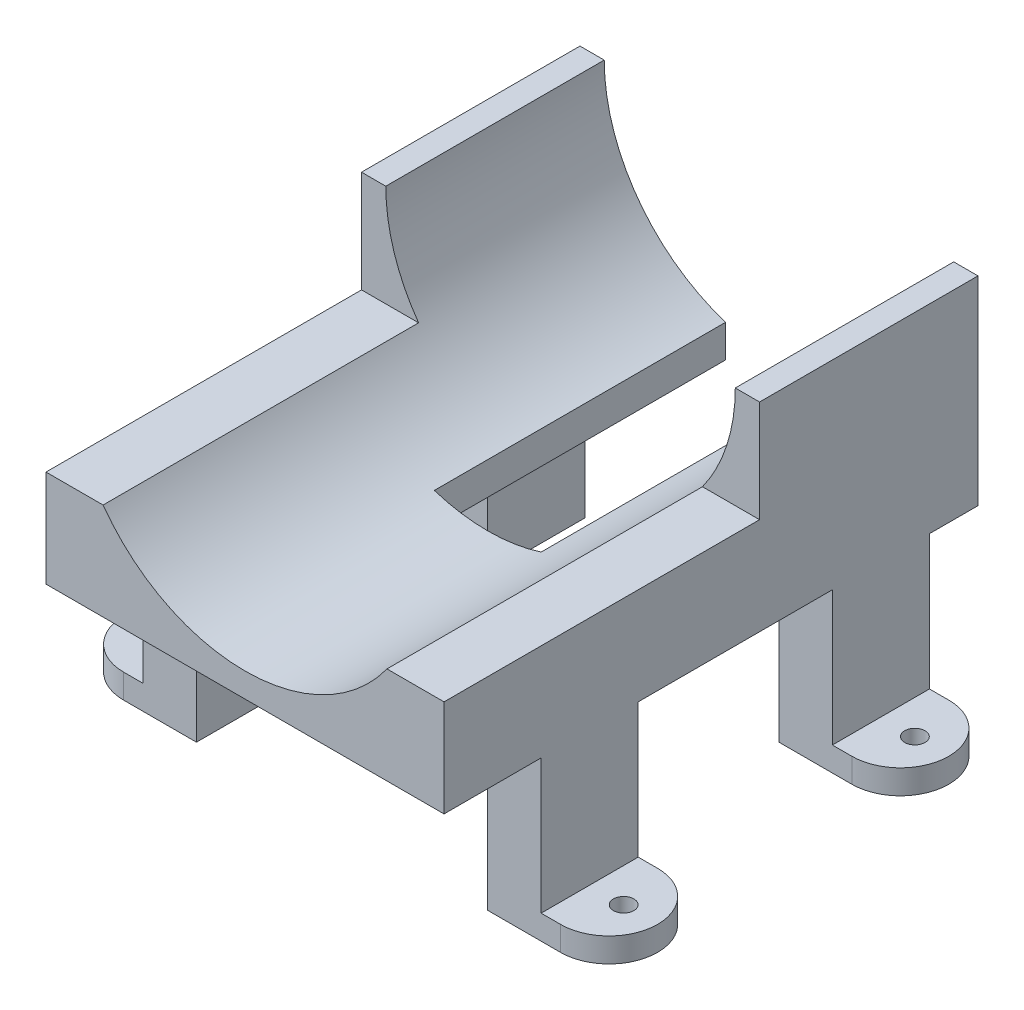
SolidWorks part; units mm, degrees
ref_plane "前基準面" through (0, 0, 0) normal (0, 0, 1) x (1, 0, 0)
ref_plane "上基準面" through (0, 0, 0) normal (0, 1, 0) x (1, 0, 0)
ref_plane "右基準面" through (0, 0, 0) normal (1, 0, 0) x (0, 0, -1)
sketch "草圖1" plane through (0, 0, 0) normal (0, 0, 1) x (1, 0, 0)
  line L0 (-41, 0) -> (41, 0) construction
  line L1 (-41, 0) -> (-41, -41)
  line L2 (-41, -41) -> (41, -41)
  line L3 (41, -41) -> (41, 0)
  circle A0 centre (0, 0) radius 36
  arc A1 (41, 0) -> (-41, 0) centre (0, 0) ccw
  circle A2 centre (0, 0) radius 41 construction
  dimension "D1" = 72
  dimension "D2" = 5
extrude "填料-伸長1" add sketch "草圖1" along normal blind 90
sketch "草圖2" plane through (0, 0, 0) normal (0, 0, 1) x (1, 0, 0)
  line L0 (0, 42.9462) -> (0, -46.3268) construction
  line L2 (11, -34.2783) -> (-11, -34.2783)
  line L3 (11, -34.2783) -> (11, -41)
  line L4 (11, -41) -> (-11, -41)
  line L5 (-11, -34.2783) -> (-11, -41)
  line L6 (0, -41) -> (0, -34.2783) construction
  line L7 (11, -37.6391) -> (-11, -37.6391) construction
  circle A0 centre (0, 0) radius 36 construction
  circle A1 centre (0, 0) radius 41 construction
  point P3 (0, -37.6391)
  dimension "D1" = 22
extrude "除料-伸長1" cut sketch "草圖2" along normal blind 60
sketch "草圖3" plane through (0, 0, 0) normal (1, 0, 0) x (0, 0, -1)
  line L1 (0, 41) -> (-90, 41)
  line L2 (0, 41) -> (0, 0)
  line L3 (0, 0) -> (-45, 0)
  line L4 (-90, 41) -> (-90, -21)
  line L5 (-90, -41) -> (-90, 0) construction
  line L8 (-90, -21) -> (-45, -21)
  line L9 (-45, -21) -> (-45, 0)
  dimension "D3" = 45
  dimension "D1" = 21
  dimension "D2" = 90
extrude "除料-伸長2" cut sketch "草圖3" against normal through all both and the other way through all
sketch "草圖4" plane through (0, 0, 90) normal (0, 0, 1) x (1, 0, 0)
  line L0 (-47.0781, 0) -> (47.0781, 0) construction
  line L5 (-30, -73.7) -> (-30, -27.9464)
  line L6 (0, 52.2232) -> (0, -44.5988) construction
  line L10 (30, -73.7) -> (30, -27.9464)
  line L12 (29.2404, -21) -> (41, -21) construction
  line L13 (-41, -68.7) -> (-55, -68.7)
  line L15 (-30, -73.7) -> (-55, -73.7)
  line L16 (-55, -68.7) -> (-55, -73.7)
  line L17 (41, -68.7) -> (55, -68.7)
  line L19 (30, -73.7) -> (55, -73.7)
  line L20 (55, -68.7) -> (55, -73.7)
  line L21 (35.2136, -21) -> (41, -21)
  line L22 (-41, -21) -> (-29.2404, -21) construction
  line L23 (-41, -21) -> (-35.2136, -21)
  line L24 (-41, -21) -> (-41, -68.7)
  line L25 (41, -21) -> (41, -68.7)
  line L26 (-41, -41) -> (41, -41) construction
  arc A0 (-35.2136, -21) -> (35.2136, -21) centre (0, 0) ccw construction
  arc A3 (41, 0) -> (-41, 0) centre (0, 0) ccw construction
  arc A4 (-35.2136, -21) -> (-30, -27.9464) centre (0, 0) ccw
  arc A5 (30, -27.9464) -> (35.2136, -21) centre (0, 0) ccw
  dimension "D5" = 82
  dimension "D1" = 5
  dimension "D2" = 32.7
  dimension "D3" = 60
  dimension "D4" = 25
extrude "填料-伸長3" add sketch "草圖4" against normal blind 20
sketch "草圖5" plane through (0, -68.7, 0) normal (0, 1, 0) x (1, 0, 0)
  line L0 (-55, -80) -> (55, -80) construction
  line L1 (-55, -70) -> (-55, -90) construction
  line L2 (55, -70) -> (55, -90) construction
  line L3 (0, 0) -> (0, -88.7499) construction
  line L4 (-41, -90) -> (-55, -90) construction
  line L10 (41, -70) -> (41, -90) construction
  line L12 (41, -90) -> (45, -90) construction
  line L13 (55, -90) -> (41, -90) construction
  line L14 (41, -70) -> (45, -70) construction
  line L15 (55, -70) -> (41, -70) construction
  line L16 (45, -70) -> (45, -66.8515)
  line L17 (45, -66.8515) -> (57.6758, -66.8515)
  line L18 (57.6758, -66.8515) -> (57.6758, -92.0469)
  line L19 (57.6758, -92.0469) -> (45, -92.0469)
  line L20 (45, -92.0469) -> (45, -90)
  line L21 (-57.6758, -92.0469) -> (-45, -92.0469)
  line L22 (-57.6758, -66.8515) -> (-57.6758, -92.0469)
  line L23 (-45, -66.8515) -> (-57.6758, -66.8515)
  line L24 (-45, -70) -> (-45, -66.8515)
  line L25 (-45, -92.0469) -> (-45, -90)
  circle A0 centre (-48, -80) radius 2.1
  circle A1 centre (48, -80) radius 2.1
  arc A2 (45, -70) -> (45, -90) centre (45, -80) cw
  arc A3 (-45, -70) -> (-45, -90) centre (-45, -80) ccw
  point P17 (-48, -90)
  dimension "D1" = 4.2
extrude "除料-伸長3" cut sketch "草圖5" against normal through all
pattern_linear "直線複製排列1" count 2 spacing 60 along (0, 0, -1) of "填料-伸長3", "除料-伸長3"
sketch "草圖6" plane through (0, 0, 90) normal (0, 0, 1) x (1, 0, 0)
  line L0 (-29.2404, -21) -> (-41, -21)
  line L1 (-41, -21) -> (-41, -41)
  line L2 (-41, -21) -> (-41, -68.7) construction
  line L3 (-41, -41) -> (41, -41)
  line L4 (41, -68.7) -> (41, -21) construction
  line L5 (41, -41) -> (41, -21)
  line L6 (41, -21) -> (29.2404, -21)
  line L7 (-30, -41) -> (30, -41) construction
  circle A0 centre (0, 0) radius 36 construction
  arc A1 (-29.2404, -21) -> (29.2404, -21) centre (0, 0) ccw
  point P16 (0, -36)
  dimension "D1" = 15
  dimension "D2" = 21
extrude "填料-伸長4" add sketch "草圖6" along normal blind 20
